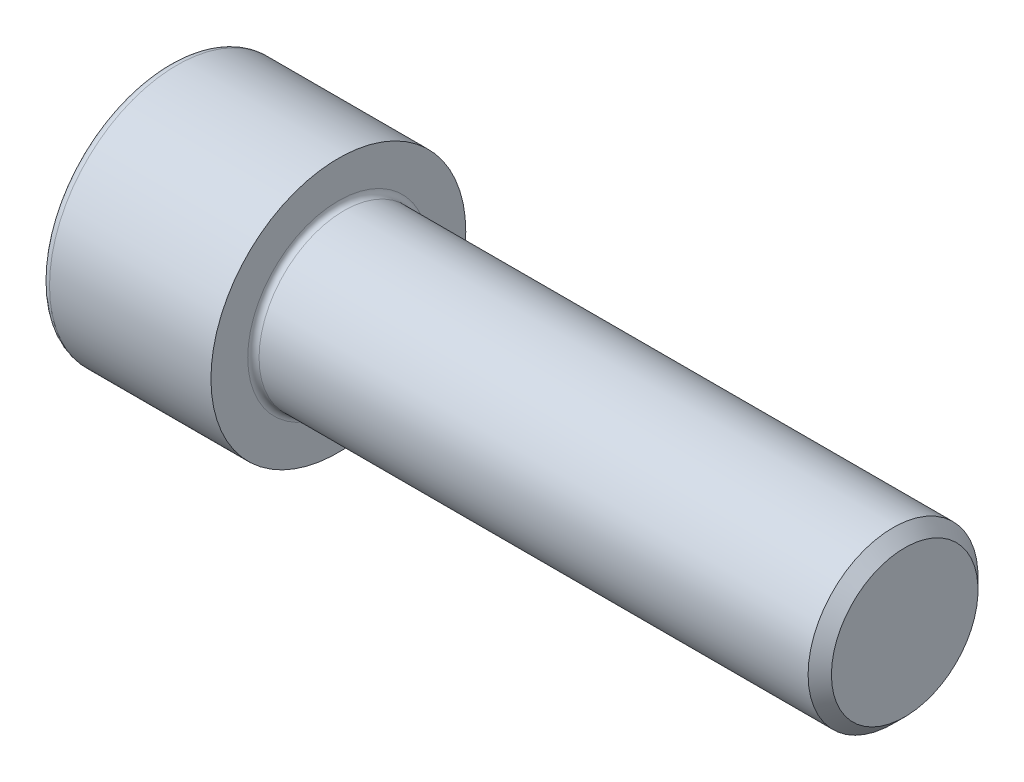
SolidWorks part; units mm, degrees
revolve "Base-Revolve" add sketch "BodySke"
sketch "BodySke" plane through (0, 0, 0) normal (0, 0, 1) x (1, 0, 0)
  line L0 (0, 0) -> (0, 18)
  line L1 (0, 18) -> (24, 18)
  line L2 (24, 18) -> (24, 12)
  line L3 (24, 12) -> (102.352, 12)
  line L4 (104, 10.352) -> (104, 0)
  line L5 (104, 0) -> (0, 0)
  line L6 (-31.75, 0) -> (127, 0) construction
  line L8 (104, 10.352) -> (102.352, 12)
  line L10 (104, -10.352) -> (102.352, -12) construction
  line L11 (27, 9.525) -> (27, 3.175) construction
  line L12 (44, 9.525) -> (44, 3.175) construction
  line L13 (44, 9.525) -> (44, 3.175) construction
  dimension "Head_ht" = 24
  dimension "Length" = 80
  dimension "Body_ch_ang" = 45
  dimension "Diameter" = 24
  dimension "Minor_dia" = 20.704
  dimension "Advance" = 3
  dimension "Thread_nom" = 60
  dimension "Thread_length" = 60
  dimension "Head_dia" = 36
cosmetic thread "ThreadCosmetic" [suppressed]
fillet "Fillet1" radius 0.8 1 edges at (24, 0, 12)
fillet "Fillet2" radius 1.2 1 edges at (0, 0, 18)
ref_plane "Plane1" through (0, 0, 0) normal (0, 0, 1) x (1, 0, 0)
ref_plane "Plane2" through (0, 0, 0) normal (0, 1, 0) x (1, 0, 0)
ref_plane "Plane3" through (0, 0, 0) normal (1, 0, 0) x (0, 0, -1)
sketch "Sketch2" plane through (0, 0, 0) normal (0, 0, 1) x (1, 0, 0)
  line L0 (0, 9.6375) -> (12.573, 9.6375)
  line L1 (12.573, 9.6375) -> (18.1372, 0)
  line L2 (-31.75, 0) -> (127, 0) construction
  line L3 (18.1372, 0) -> (0, 0)
  line L4 (0, 0) -> (0, 9.6375)
  line L6 (0, 0) -> (47.625, 0) construction
  dimension "D1" = 9.6375
  dimension "D2" = 60
  dimension "Depth" = 12.573
revolve "Hex-PreBroach" cut sketch "Sketch2" angle 360 about L6
sketch "Sketch3" plane through (0, 0, 0) normal (-1, 0, 0) x (0, 0.5, 0.866)
  line L0 (5.5642, 9.6375) -> (-5.5642, 9.6375)
  line L1 (-5.5642, 9.6375) -> (-11.1284, 0)
  line L2 (5.5642, 9.6375) -> (11.1284, 0)
  line L3 (5.5642, -9.6375) -> (11.1284, 0)
  line L4 (5.5642, -9.6375) -> (-5.5642, -9.6375)
  line L5 (-5.5642, -9.6375) -> (-11.1284, 0)
  dimension "D1" = 9.6375
  dimension "D2" = 9.6375
  dimension "Hex_size" = 19.275
extrude "Hex" cut sketch "Sketch3" against normal blind 12.573
sketch "ThdSchSke" plane through (0, 0, 0) normal (0, 0, 1) x (1, 0, 0)
  line L0 (44, -10.352) -> (42.8461, -12)
  line L1 (44, -10.352) -> (45.1539, -12)
  line L2 (45.1539, -12) -> (45.1539, -15)
  line L3 (-3.175, 0) -> (5.1513, 0) construction
  line L4 (0, 16.8) -> (0, -16.8) construction
  line L5 (45.1539, -15) -> (42.8461, -15)
  line L6 (42.8461, -15) -> (42.8461, -12)
  dimension "Thread_minor" = 20.704
  dimension "Diameter" = 24
  dimension "Start" = 44
revolve "ThreadSchematic" [suppressed] cut sketch "ThdSchSke" angle 360 about L3
pattern_linear "ThdSchPat" [suppressed]
equation "\"D2@Sketch3\" = \"Hex_size@Sketch3\" / 2"
equation "\"D1@Sketch3\" = \"Hex_size@Sketch3\" / 2"
equation "\"D1@Sketch2\" = \"Hex_size@Sketch3\" / 2"
equation "\"Thread_minor@ThreadCosmetic\"  =  \"Minor_dia@BodySke\""
equation "\"Depth@Sketch2\" =  \"Key_eng@Hex\""
equation "\"Thread_length@ThreadCosmetic\" = ((sgn( (\"Length@BodySke\" - \"Advance@BodySke\" * 3.0) - \"Thread_nom@BodySke\" )-1)*( (\"Length@BodySke\" - \"Advance@BodySke\" * 3.0) - \"Thread_nom@BodySke\" ))/-2+ \"Thread_nom@BodySke\""
equation "\"Thread_minor@ThdSchSke\" = \"Minor_dia@BodySke\""
equation "\"Diameter@ThdSchSke\" = \"Diameter@BodySke\""
equation "\"Overcut@ThdSchSke\" = \"Diameter@BodySke\" * 1.25"
equation "\"Start@ThdSchSke\" = \"Head_ht@BodySke\" + \"Length@BodySke\" - \"Thread_length@ThreadCosmetic\"  '---Non-countersunk---"
equation "\"Num_threads@ThdSchPat\" = int( \"Thread_length@ThreadCosmetic\" / \"Advance@BodySke\" + 0.999 )  + 1"
equation "\"Advance@ThdSchPat\" = \"Thread_length@ThreadCosmetic\" /  (\"Num_threads@ThdSchPat\" - 1) 'relax it"
equation "\"Num_threads@ThdSchPat\" = \"Num_threads@ThdSchPat\" - sgn( \"Num_threads@ThdSchPat\" - 1) '---chamfered tips only---"
